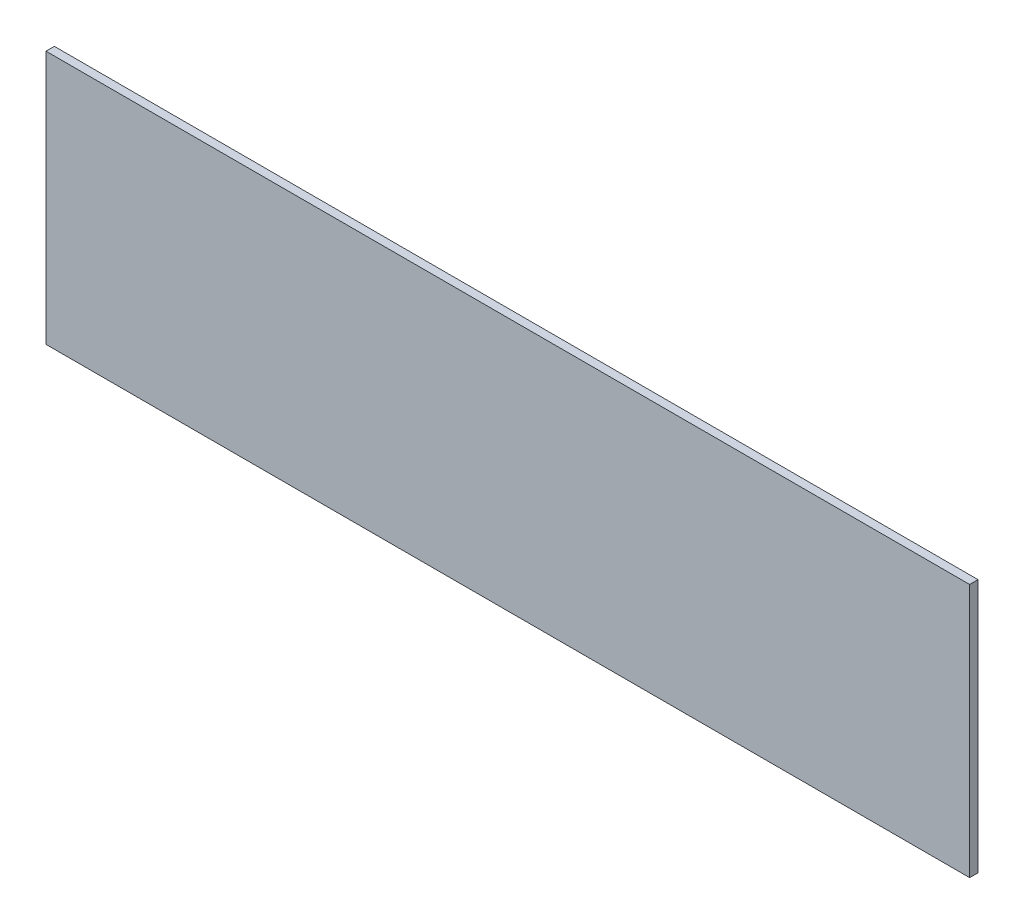
SolidWorks part; units mm, degrees
ref_plane "Front" through (0, 0, 0) normal (0, 0, 1) x (1, 0, 0)
ref_plane "Top" through (0, 0, 0) normal (0, 1, 0) x (1, 0, 0)
ref_plane "Right" through (0, 0, 0) normal (1, 0, 0) x (0, 0, -1)
sketch "草图1" plane through (0, 0, 0) normal (0, 0, 1) x (1, 0, 0)
  line L1 (-113.5033, 11.5656) -> (51.9967, 11.5656)
  line L2 (-113.5033, 11.5656) -> (-113.5033, -33.9344)
  line L3 (-113.5033, -33.9344) -> (51.9967, -33.9344)
  line L4 (51.9967, 11.5656) -> (51.9967, -33.9344)
  dimension "D1" = 165.5
  dimension "D2" = 45.5
extrude "凸台-拉伸1" add sketch "草图1" along normal blind 1.5
